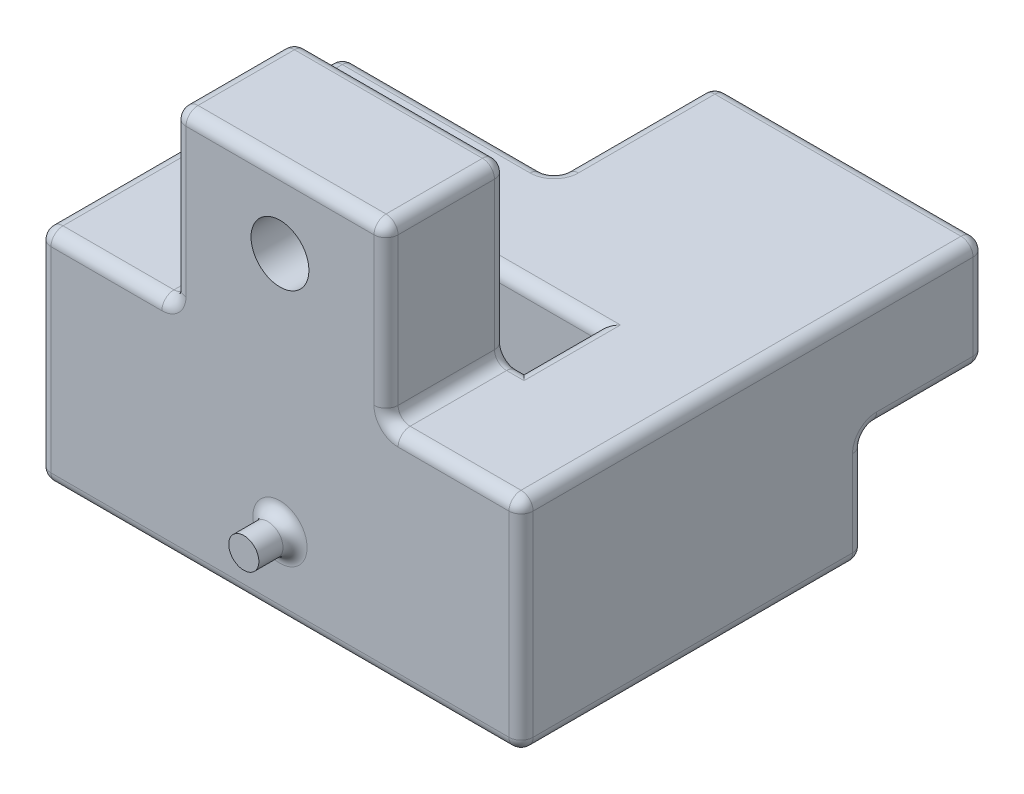
SolidWorks part; units mm, degrees
material "ABS"
ref_plane "X-Y Datum" through (0, 0, 0) normal (0, 0, 1) x (1, 0, 0)
ref_plane "X-Z Datum" through (0, 0, 0) normal (0, 1, 0) x (1, 0, 0)
ref_plane "Y-Z Datum" through (0, 0, 0) normal (1, 0, 0) x (0, 0, -1)
sketch "Sketch1" plane through (0, 0, 0) normal (0, 1, 0) x (1, 0, 0)
  line L0 (0, 10.1259) -> (0, 23.1529) construction
  line L1 (-10.25, -3) -> (10.25, -3)
  line L2 (-10.25, -3) -> (-10.25, 3)
  line L3 (-10.25, 3) -> (10.25, 3)
  line L4 (10.25, -3) -> (10.25, 3)
  line L5 (-10.25, -3) -> (10.25, 3) construction
  line L6 (-10.25, 3) -> (10.25, -3) construction
  line L12 (-20, -13) -> (20, -13)
  line L13 (0, 0) -> (13.3641, 0) construction
  line L14 (-20, -13) -> (-20, 25.5)
  line L15 (-20, 25.5) -> (20, 25.5)
  line L16 (20, -13) -> (20, 25.5)
  circle A0 centre (-9.6, 17.5) radius 2.1
  point P0 (0, 0)
  point P6 (0, 0)
  dimension "D5" = 4.2
  dimension "D1" = 20.5
  dimension "D2" = 6
  dimension "D3" = 38.5
  dimension "D4" = 40
  dimension "D6" = 9.6
  dimension "D7" = 20.5
  dimension "D8" = 10
extrude "Boss-Extrude1" add sketch "Sketch1" along normal blind 18.25
sketch "Sketch2" plane through (0, 0, 13) normal (0, 0, 1) x (1, 0, 0)
  line L0 (-20, 18.25) -> (20, 18.25) construction
  line L1 (-8.7987, 4) -> (8.7987, 4)
  line L2 (-8.7987, 4) -> (-8.7987, 32.5)
  line L3 (-8.7987, 32.5) -> (8.7987, 32.5)
  line L4 (8.7987, 4) -> (8.7987, 32.5)
  line L5 (-8.7987, 4) -> (8.7987, 32.5) construction
  line L6 (-8.7987, 32.5) -> (8.7987, 4) construction
  line L7 (-20, 0) -> (20, 0) construction
  circle A0 centre (0, 6.25) radius 1.25
  circle A1 centre (0, 26.25) radius 0.693
  point P0 (0, 18.25)
  dimension "D2" = 2.5
  dimension "D1" = 32.5
  dimension "D3" = 12
  dimension "D4" = 20
extrude "Boss-Extrude2" add sketch "Sketch2" against normal up to surface (10 mm away) up to face at (0, 9.125, 3)
sketch "Sketch3" plane through (0, 0, 13) normal (0, 0, 1) x (1, 0, 0)
  circle A0 centre (0, 6.25) radius 1.25
  circle A1 centre (0, 26.25) radius 0.693 construction
  dimension "D1" = 2.5
  dimension "D2" = 20
extrude "Boss-Extrude3" add sketch "Sketch3" along normal blind 3
sketch "Sketch4" plane through (0, 0, 0) normal (0, -1, 0) x (1, 0, 0)
  line L0 (-20, 13) -> (20, 13) construction
  circle A0 centre (0, 8) radius 1.25
  dimension "D1" = 2.5
  dimension "D2" = 5
extrude "Boss-Extrude4" add sketch "Sketch4" along normal blind 3
sketch "Sketch5" plane through (0, 18.25, 0) normal (0, 1, 0) x (1, 0, 0)
  line L0 (-20, 25.5) -> (-20, -13) construction
  line L1 (-20, 12.1701) -> (-2.4187, 12.1701)
  line L2 (-20, 12.1701) -> (-20, 25.5)
  line L3 (-20, 25.5) -> (-2.4187, 25.5)
  line L4 (-2.4187, 12.1701) -> (-2.4187, 25.5)
  line L5 (20, 25.5) -> (-20, 25.5) construction
extrude "Cut-Extrude1" cut sketch "Sketch5" against normal blind 15.24
chamfer "Chamfer1" distance 10 angle 45 1 edges at (-20, 1.505, -25.5)
sketch "Sketch6" plane through (0, 0, 0) normal (0, -1, 0) x (1, 0, 0)
  line L1 (20, -25.5) -> (3.1156, -25.5)
  line L2 (20, -25.5) -> (20, -15.5)
  line L3 (20, -15.5) -> (3.1156, -15.5)
  line L4 (3.1156, -25.5) -> (3.1156, -15.5)
extrude "Cut-Extrude2" cut sketch "Sketch6" against normal blind 9.125
fillet "Fillet1" radius 1 54 edges at (3.1156, 0, -20.5) (8.7987, 25.375, 3) (8.7987, 25.375, 13) (-10.25, 0, 0) (0, 0, -3) (10.25, 0, 0) (0, 0, 3) (-11.2094, 3.01, -12.1701) (-8.7987, 32.5, 8) (0, 32.5, 3) (0, 32.5, 13) (8.7987, 32.5, 8) (-15, 0, -20.5) (-15, 3.01, -20.5) (20, 9.125, -20.5) (20, 0, -1.25) (20, 4.5625, -15.5) (11.5578, 9.125, -15.5) (3.1156, 4.5625, -15.5) (11.5578, 0, -15.5) (0.693, 26.25, 13) (20, 9.125, 13) (0, 0, 13) (-8.7987, 25.375, 13) (-8.7987, 25.375, 3) (-1.25, 6.25, 13) (20, 18.25, -6.25) (14.3993, 18.25, 13) (8.7987, 18.25, 8) (9.5243, 18.25, 3) (10.25, 18.25, 0) (0, 18.25, -3) (-10.25, 18.25, 0) (-9.5243, 18.25, 3) (-8.7987, 18.25, 8) (-14.3993, 18.25, 13) (-11.2094, 18.25, -12.1701) (-20, 10.63, -12.1701) (-20, 18.25, 0.4149) (-20, 9.125, 13) (-20, 0, -1.25) (-20, 1.505, -15.5) (-20, 3.01, -13.8351) (20, 13.6875, -25.5) (8.7906, 18.25, -25.5) (-6.2094, 3.01, -25.5) (-10, 1.505, -25.5) (-3.4422, 0, -25.5) (3.1156, 4.5625, -25.5) (11.5578, 9.125, -25.5) (-2.4187, 10.63, -12.1701) (-2.4187, 3.01, -18.8351) (-2.4187, 10.63, -25.5) (-2.4187, 18.25, -18.8351)
hole_wizard "M4 Clearance Hole1" positions "Sketch7" profile "Sketch8" hole size "M4" standard "ANSI Metric" end condition through all
sketch "Sketch7" plane through (0, 0, 3) normal (0, 0, -1) x (-1, 0, 0)
  point P0 (0, 26.25)
sketch "Sketch8" plane through (0, 26.25, 3) normal (1, 0, 0) x (0, 1, 0)
  line L0 (0, 0) -> (0, 13)
  line L1 (0, 13) -> (2.4, 13)
  line L2 (2.4, 13) -> (2.4, 0)
  line L5 (2.4, 0) -> (0, 0)
  line L11 (0, -6.35) -> (0, 107.95) construction
  dimension "Thru Hole Dia." = 4.8
  dimension "Thru Hole Depth" = 13
